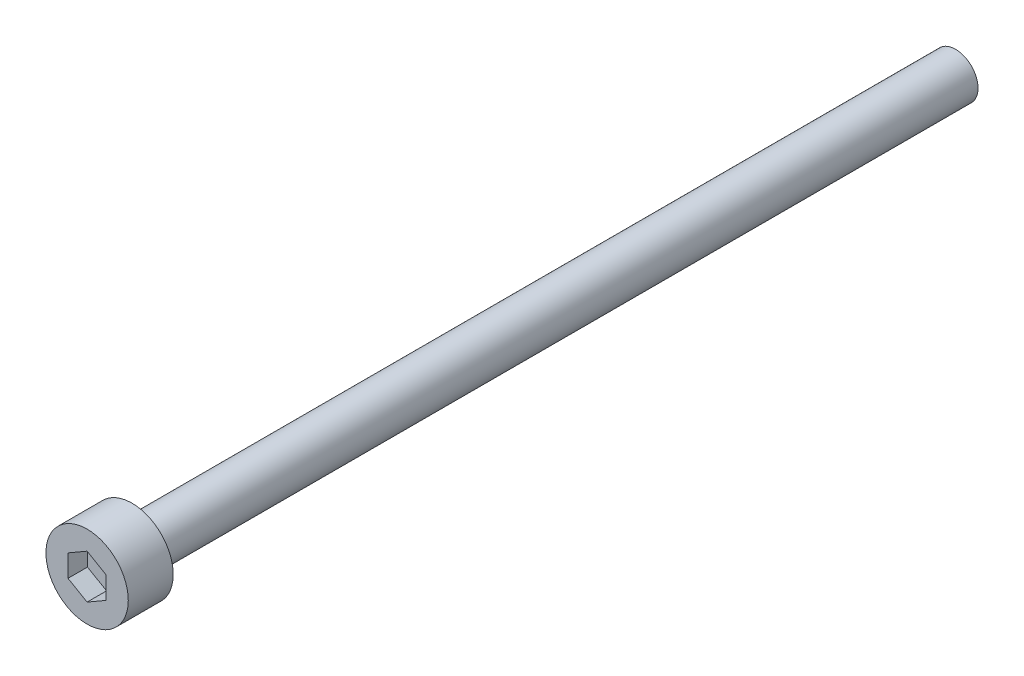
SolidWorks part; units mm, degrees
material "AISI 304"
ref_plane "Front Plane" through (0, 0, 0) normal (0, 0, 1) x (1, 0, 0)
ref_plane "Top Plane" through (0, 0, 0) normal (0, 1, 0) x (1, 0, 0)
ref_plane "Right Plane" through (0, 0, 0) normal (1, 0, 0) x (0, 0, -1)
sketch "草图1" plane through (0, 0, 0) normal (0, 0, 1) x (1, 0, 0)
  circle A0 centre (0, 0) radius 2.75
  dimension "D1" = 5.5
extrude "凸台-拉伸1" add sketch "草图1" along normal blind 3
sketch "草图2" plane through (0, 0, 3) normal (0, 0, 1) x (1, 0, 0)
  line L1 (1.275, -0.7361) -> (1.275, 0.7361)
  line L2 (1.275, 0.7361) -> (0, 1.4722)
  line L3 (0, 1.4722) -> (-1.275, 0.7361)
  line L4 (-1.275, 0.7361) -> (-1.275, -0.7361)
  line L5 (-1.275, -0.7361) -> (0, -1.4722)
  line L6 (0, -1.4722) -> (1.275, -0.7361)
  circle A0 centre (0, 0) radius 1.275 construction
  dimension "D1" = 2.55
extrude "切除-拉伸1" cut sketch "草图2" against normal blind 1.3
sketch "草图3" plane through (0, 0, 0) normal (0, 0, -1) x (-1, 0, 0)
  circle A0 centre (0, 0) radius 1.5
  dimension "D1" = 3
extrude "凸台-拉伸2" add sketch "草图3" along normal blind 55
cosmetic thread "装饰螺纹线1" parameters "D2"=3
